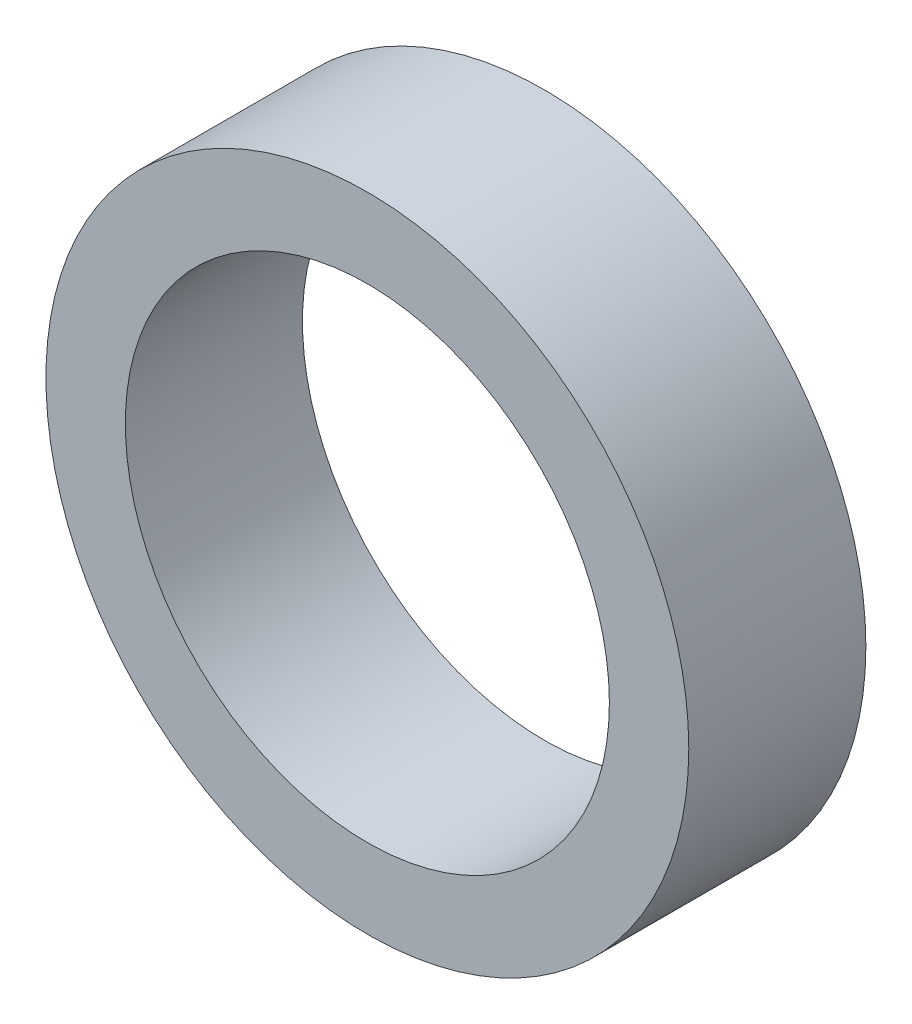
SolidWorks part; units mm, degrees
ref_plane "Ebene vorne" through (0, 0, 0) normal (0, 0, 1) x (1, 0, 0)
ref_plane "Ebene oben" through (0, 0, 0) normal (0, 1, 0) x (1, 0, 0)
ref_plane "Ebene rechts" through (0, 0, 0) normal (1, 0, 0) x (0, 0, -1)
sketch "Skizze1" plane through (0, 0, 0) normal (0, 0, 1) x (1, 0, 0)
  circle A0 centre (0, 0) radius 4.1
  circle A1 centre (0, 0) radius 5.445
  dimension "D1" = 10.89
  dimension "D2" = 8.2
extrude "Aufsatz-Linear austragen1" add sketch "Skizze1" along normal blind 3
